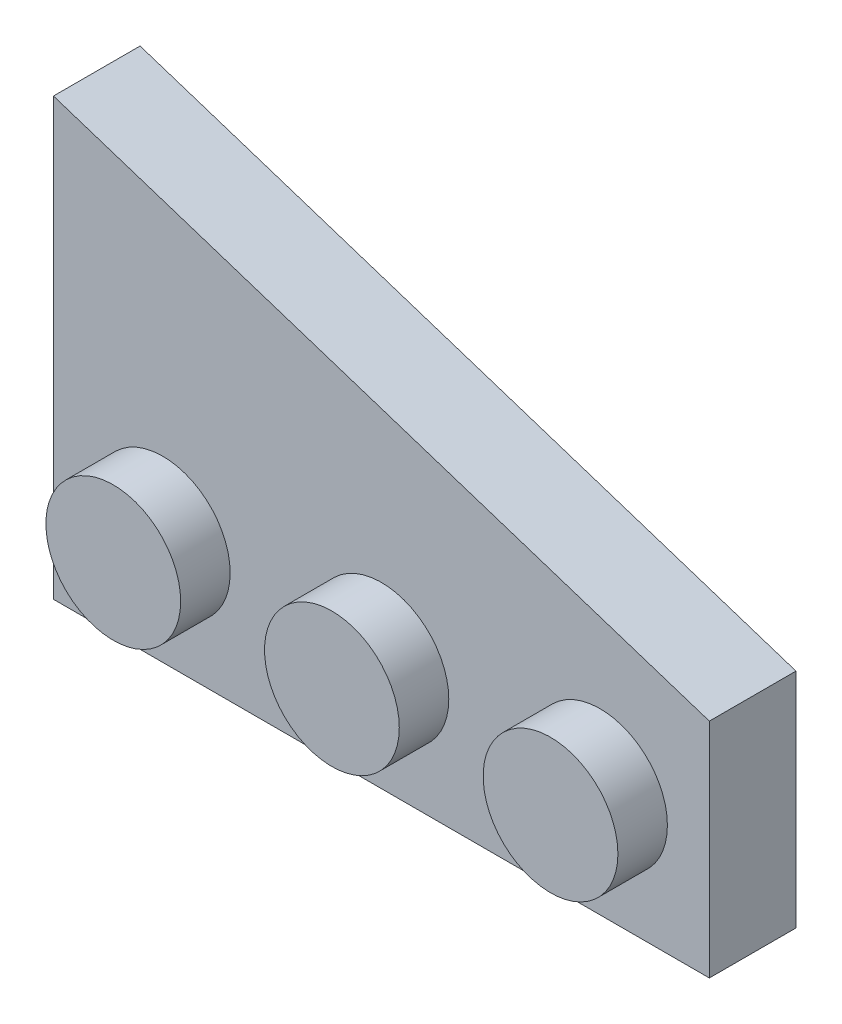
SolidWorks part; units mm, degrees
ref_plane "Front Plane" through (0, 0, 0) normal (0, 0, 1) x (1, 0, 0)
ref_plane "Top Plane" through (0, 0, 0) normal (0, 1, 0) x (1, 0, 0)
ref_plane "Right Plane" through (0, 0, 0) normal (1, 0, 0) x (0, 0, -1)
sketch "Sketch1" plane through (0, 0, 0) normal (0, 0, 1) x (1, 0, 0)
  line L0 (0, 0) -> (23.85, 0)
  line L1 (23.85, 0) -> (23.85, 8.09)
  line L2 (23.85, 8.09) -> (0, 15.85)
  line L3 (0, 15.85) -> (0, 0)
  dimension "D1" = 23.85
  dimension "D2" = 8.09
  dimension "D3" = 15.85
extrude "Boss-Extrude1" add sketch "Sketch1" against normal blind 3.15
sketch "Sketch2" plane through (0, 0, 0) normal (0, 0, 1) x (1, 0, 0)
  line L1 (0, 15.85) -> (0, 0) construction
  line L3 (0, 0) -> (23.85, 0) construction
  circle A0 centre (3.975, 4.045) radius 2.45
  circle A1 centre (11.925, 4.045) radius 2.45
  circle A2 centre (19.875, 4.045) radius 2.45
  dimension "D1" = 4.9
  dimension "D5" = 7.95
  dimension "D2" = 3.975
  dimension "D3" = 4.045
  dimension "D4" = 3
extrude "Boss-Extrude2" add sketch "Sketch2" along normal blind 1.8
shell "Shell1" thickness 1.5
